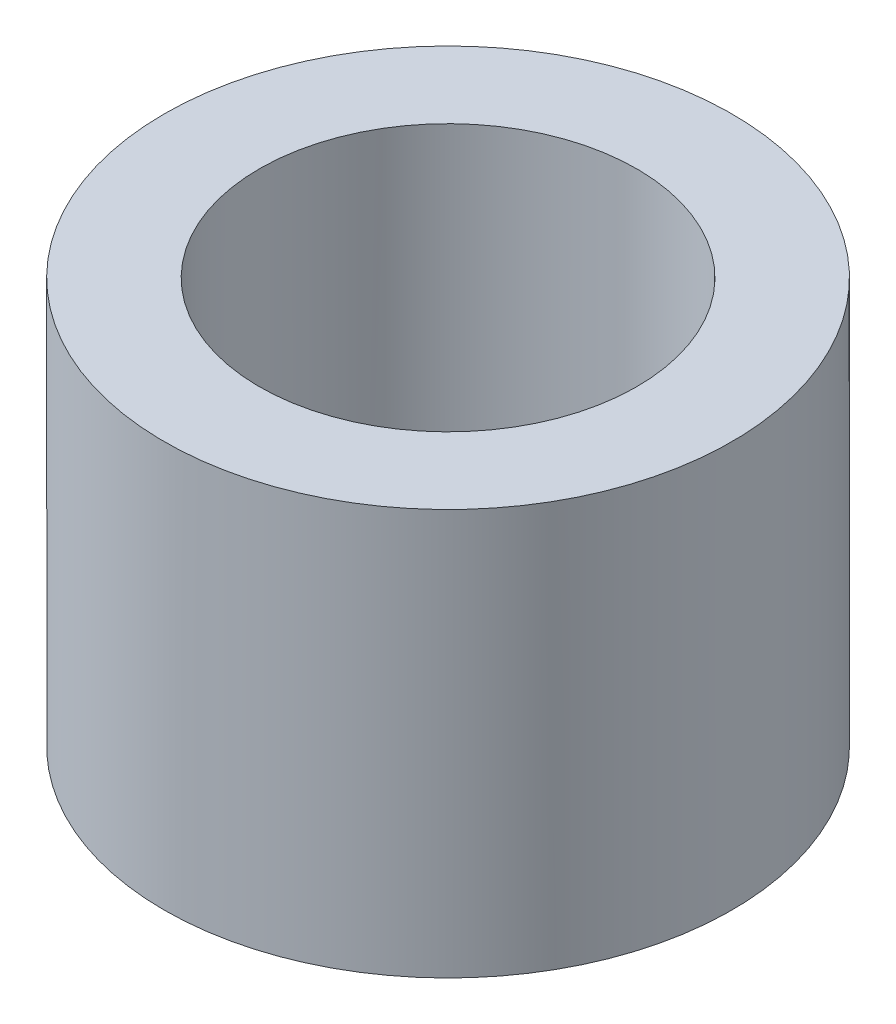
SolidWorks part; units mm, degrees
material "PLA"
ref_plane "Front Plane" through (0, 0, 0) normal (0, 0, 1) x (1, 0, 0)
ref_plane "Top Plane" through (0, 0, 0) normal (0, 1, 0) x (1, 0, 0)
ref_plane "Right Plane" through (0, 0, 0) normal (1, 0, 0) x (0, 0, -1)
sketch "Sketch1" plane through (0, 0, 0) normal (0, 1, 0) x (1, 0, 0)
  circle A0 centre (0, 0) radius 1.5875
  circle A1 centre (0, 0) radius 2.3875
  dimension "D1" = 3.175
  dimension "D2" = 0.8
extrude "Boss-Extrude1" add sketch "Sketch1" along normal up to surface (3.4125 mm away)
